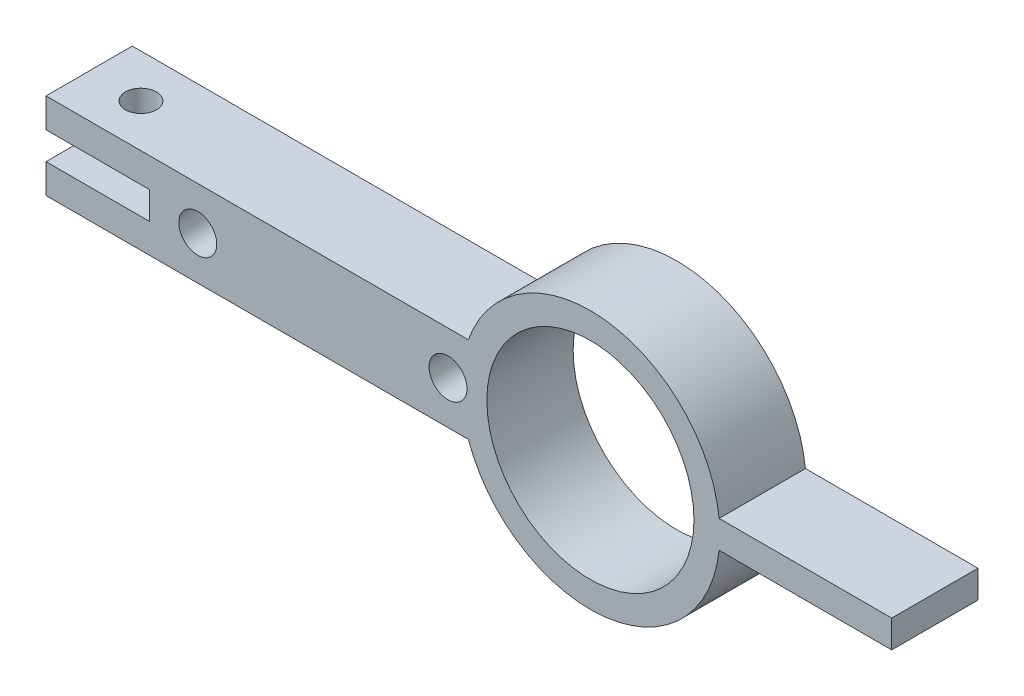
SolidWorks part; units mm, degrees
ref_plane "Front Plane" through (0, 0, 0) normal (0, 0, 1) x (1, 0, 0)
ref_plane "Top Plane" through (0, 0, 0) normal (0, 1, 0) x (1, 0, 0)
ref_plane "Right Plane" through (0, 0, 0) normal (1, 0, 0) x (0, 0, -1)
sketch "Sketch1" plane through (0, 0, 0) normal (0, 0, 1) x (1, 0, 0)
  line L0 (-31.5428, 2.5) -> (-7.0711, 2.5)
  line L1 (-31.5428, -2.5) -> (-7.0711, -2.5)
  line L2 (7.4572, 0.8) -> (17.4572, 0.8)
  line L3 (7.4572, -0.8) -> (17.4572, -0.8)
  line L4 (-31.5428, 2.5) -> (-31.5428, 0.8)
  line L5 (17.4572, 0.8) -> (17.4572, -0.8)
  line L6 (-7.5, 0) -> (7.5, 0) construction
  line L7 (-31.5428, 0.8) -> (-25.5428, 0.8)
  line L8 (-25.5428, 0.8) -> (-25.5428, -0.8)
  line L9 (-25.5428, -0.8) -> (-31.5428, -0.8)
  line L10 (-31.5428, -0.8) -> (-31.5428, -2.5)
  line L11 (-7.0711, 2.5) -> (-7.0711, -2.5) construction
  arc A0 (-7.0711, -2.5) -> (7.4572, -0.8) centre (0, 0) ccw
  arc A1 (7.4572, 0.8) -> (-7.0711, 2.5) centre (0, 0) ccw
  point P12 (-7.0711, 0)
  point P18 (17.4572, 0)
  dimension "D1" = 7.5
  dimension "D2" = 5
  dimension "D3" = 49
  dimension "D4" = 1.6
  dimension "D5" = 6
  dimension "D6" = 10
extrude "Boss-Extrude1" add sketch "Sketch1" along normal mid plane 5
hole_wizard "Tap Drill for M12x1.5 Tap1" positions "Sketch2" profile "Sketch3" hole size "M12x1.5" standard "ISO" end condition through all
sketch "Sketch2" plane through (0, 0, 2.5) normal (0, 0, 1) x (1, 0, 0)
  point P0 (0, 0)
sketch "Sketch3" plane through (0, 0, 2.5) normal (1, 0, 0) x (0, -1, 0)
  line L0 (0, 0) -> (0, 5)
  line L1 (0, 5) -> (6, 5)
  line L2 (6, 5) -> (6, 0)
  line L5 (6, 0) -> (0, 0)
  line L11 (0, -6.35) -> (0, 107.95) construction
  dimension "Thru Hole Dia." = 12
  dimension "Thru Hole Depth" = 5
sketch "Sketch4" plane through (0, 2.5, 0) normal (0, 1, 0) x (1, 0, 0)
  line L0 (-31.5428, -2.5) -> (-25.5428, -2.5) construction
  line L1 (-31.5428, -2.5) -> (-31.5428, 2.5) construction
  point P0 (-28.5428, 0)
  point P3 (-28.5428, -2.5)
  point P6 (-31.5428, 0)
hole_wizard "Hole1" positions "Sketch5" profile "Sketch6" legacy end condition through all
sketch "Sketch5" plane through (0, 2.5, 0) normal (0, 1, 0) x (1, 0, 0)
  point P0 (-28.5428, 0)
sketch "Sketch6" plane through (-28.5428, 2.5, 0) normal (1, 0, 0) x (0, 0, 1)
  line L0 (0, 0) -> (0, 10)
  line L1 (0, 10) -> (0.9, 10)
  line L2 (0.9, 10) -> (0.9, 0)
  line L3 (0.9, 0) -> (0, 0)
  line L4 (0, 110) -> (0, -10) construction
  dimension "Diameter" = 1.8
  dimension "Depth" = 10
sketch "Sketch7" plane through (0, 0, -2.5) normal (0, 0, 1) x (1, 0, 0)
  circle A0 centre (-8.25, 0) radius 1.1 construction
  circle A1 centre (-22.75, 0) radius 1.1 construction
  circle A2 centre (-8.25, 0) radius 1.1
  circle A3 centre (-22.75, 0) radius 1.1
extrude "Cut-Extrude1" cut sketch "Sketch7" along normal through all
